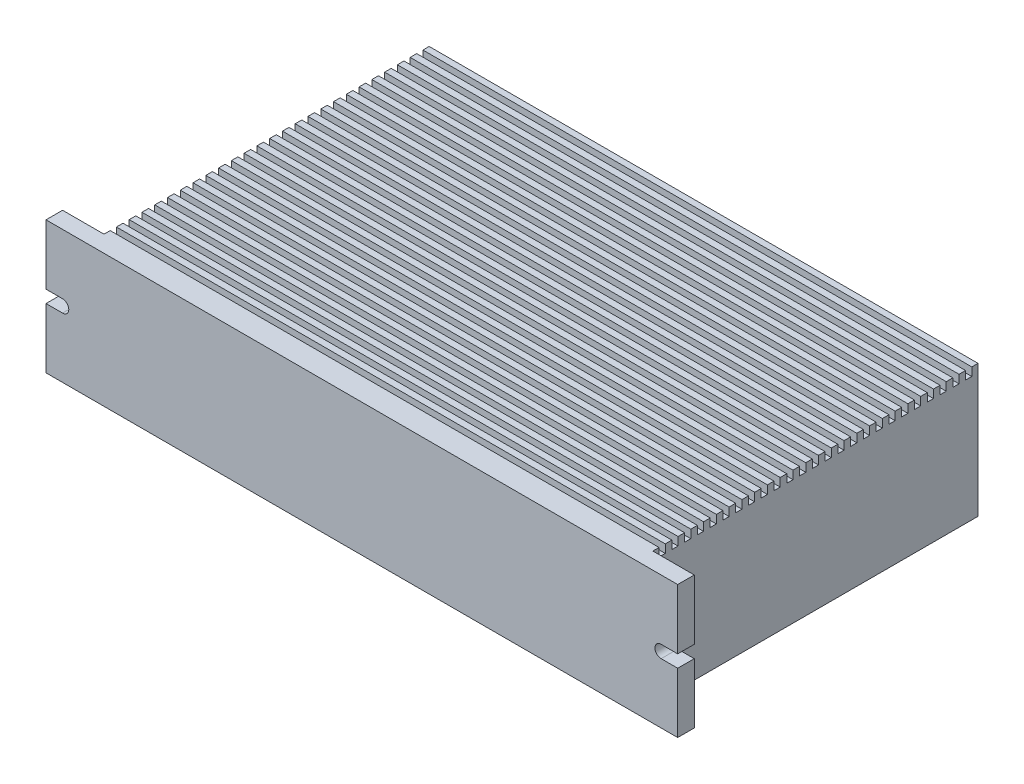
SolidWorks part; units mm, degrees
material "1060 合金"
ref_plane "前视基准面" through (0, 0, 0) normal (0, 0, 1) x (1, 0, 0)
ref_plane "上视基准面" through (0, 0, 0) normal (0, 1, 0) x (1, 0, 0)
ref_plane "右视基准面" through (0, 0, 0) normal (1, 0, 0) x (0, 0, -1)
sketch "草图1" plane through (0, 0, 0) normal (0, 1, 0) x (1, 0, 0)
  line L1 (-132.5, 82.5) -> (132.5, 82.5)
  line L2 (-132.5, 82.5) -> (-132.5, -82.5)
  line L3 (-132.5, -82.5) -> (132.5, -82.5)
  line L4 (132.5, 82.5) -> (132.5, -82.5)
  point P4 (-132.5, 0)
  point P6 (0, 82.5)
  dimension "D1" = 165
  dimension "D2" = 265
extrude "凸台-拉伸1" add sketch "草图1" along normal blind 64
sketch "草图2" plane through (0, 0, 82.5) normal (0, 0, 1) x (1, 0, 0)
  line L1 (-152.5, 64) -> (152.5, 64)
  line L2 (-152.5, 64) -> (-152.5, 35)
  line L3 (-152.5, 0) -> (152.5, 0)
  line L4 (152.5, 64) -> (152.5, 35)
  line L5 (-132.5, 64) -> (-132.5, 0) construction
  line L6 (-132.5, 0) -> (132.5, 0) construction
  line L7 (-132.5, 64) -> (132.5, 64) construction
  line L8 (152.5, 29) -> (152.5, 0)
  line L9 (-152.5, 35) -> (-144.5, 35)
  line L10 (-152.5, 29) -> (-144.5, 29)
  line L11 (0, 0) -> (0, 64) construction
  line L14 (-152.5, 35) -> (-144.5, 35)
  line L15 (-152.5, 29) -> (-144.5, 29)
  line L17 (152.5, 29) -> (144.5, 29)
  line L18 (152.5, 35) -> (144.5, 35)
  line L19 (152.5, 29) -> (144.5, 29)
  line L20 (152.5, 35) -> (144.5, 35)
  line L21 (-152.5, 29) -> (-152.5, 0)
  arc A1 (-144.5, 29) -> (-144.5, 35) centre (-144.5, 32) ccw
  arc A4 (144.5, 29) -> (144.5, 35) centre (144.5, 32) cw
  line M6 (132.5, 0) -> (132.5, 64)
  line M8 (-132.5, 64) -> (-132.5, 0)
  dimension "D3" = 3
  dimension "D1" = 29
  dimension "D2" = 20
  dimension "D4" = 8
extrude "凸台-拉伸2" add sketch "草图2" against normal blind 8 contours A1 L10 L21 L3 L1 L2 L9 M8 | L17 A4 L18 L4 L1 L3 L8 M6
sketch "草图3" plane through (0, 0, 0) normal (1, 0, 0) x (0, 0, -1)
  line L0 (-74.5, 64) -> (82.5, 64) construction
  line L1 (-71.5, 64) -> (-68.5, 64)
  line L2 (-71.5, 64) -> (-71.5, 60)
  line L3 (-71.5, 60) -> (-68.5, 60)
  line L4 (-68.5, 64) -> (-68.5, 60)
  line L5 (-74.5, 64) -> (-74.5, 35) construction
  line L6 (-65.3333, 60) -> (-62.3333, 60)
  line L7 (-62.3333, 64) -> (-62.3333, 60)
  line L8 (-65.3333, 64) -> (-62.3333, 64)
  line L9 (-65.3333, 64) -> (-65.3333, 60)
  line L10 (-59.1667, 60) -> (-56.1667, 60)
  line L11 (-56.1667, 64) -> (-56.1667, 60)
  line L12 (-59.1667, 64) -> (-56.1667, 64)
  line L13 (-59.1667, 64) -> (-59.1667, 60)
  line L14 (-53, 60) -> (-50, 60)
  line L15 (-50, 64) -> (-50, 60)
  line L16 (-53, 64) -> (-50, 64)
  line L17 (-53, 64) -> (-53, 60)
  line L18 (-46.8333, 60) -> (-43.8333, 60)
  line L19 (-43.8333, 64) -> (-43.8333, 60)
  line L20 (-46.8333, 64) -> (-43.8333, 64)
  line L21 (-46.8333, 64) -> (-46.8333, 60)
  line L22 (-40.6667, 60) -> (-37.6667, 60)
  line L23 (-37.6667, 64) -> (-37.6667, 60)
  line L24 (-40.6667, 64) -> (-37.6667, 64)
  line L25 (-40.6667, 64) -> (-40.6667, 60)
  line L26 (-34.5, 60) -> (-31.5, 60)
  line L27 (-31.5, 64) -> (-31.5, 60)
  line L28 (-34.5, 64) -> (-31.5, 64)
  line L29 (-34.5, 64) -> (-34.5, 60)
  line L30 (-28.3333, 60) -> (-25.3333, 60)
  line L31 (-25.3333, 64) -> (-25.3333, 60)
  line L32 (-28.3333, 64) -> (-25.3333, 64)
  line L33 (-28.3333, 64) -> (-28.3333, 60)
  line L34 (-22.1667, 60) -> (-19.1667, 60)
  line L35 (-19.1667, 64) -> (-19.1667, 60)
  line L36 (-22.1667, 64) -> (-19.1667, 64)
  line L37 (-22.1667, 64) -> (-22.1667, 60)
  line L38 (-16, 60) -> (-13, 60)
  line L39 (-13, 64) -> (-13, 60)
  line L40 (-16, 64) -> (-13, 64)
  line L41 (-16, 64) -> (-16, 60)
  line L42 (-9.8333, 60) -> (-6.8333, 60)
  line L43 (-6.8333, 64) -> (-6.8333, 60)
  line L44 (-9.8333, 64) -> (-6.8333, 64)
  line L45 (-9.8333, 64) -> (-9.8333, 60)
  line L46 (-3.6667, 60) -> (-0.6667, 60)
  line L47 (-0.6667, 64) -> (-0.6667, 60)
  line L48 (-3.6667, 64) -> (-0.6667, 64)
  line L49 (-3.6667, 64) -> (-3.6667, 60)
  line L50 (2.5, 60) -> (5.5, 60)
  line L51 (5.5, 64) -> (5.5, 60)
  line L52 (2.5, 64) -> (5.5, 64)
  line L53 (2.5, 64) -> (2.5, 60)
  line L54 (8.6667, 60) -> (11.6667, 60)
  line L55 (11.6667, 64) -> (11.6667, 60)
  line L56 (8.6667, 64) -> (11.6667, 64)
  line L57 (8.6667, 64) -> (8.6667, 60)
  line L58 (14.8333, 60) -> (17.8333, 60)
  line L59 (17.8333, 64) -> (17.8333, 60)
  line L60 (14.8333, 64) -> (17.8333, 64)
  line L61 (14.8333, 64) -> (14.8333, 60)
  line L62 (21, 60) -> (24, 60)
  line L63 (24, 64) -> (24, 60)
  line L64 (21, 64) -> (24, 64)
  line L65 (21, 64) -> (21, 60)
  line L66 (27.1667, 60) -> (30.1667, 60)
  line L67 (30.1667, 64) -> (30.1667, 60)
  line L68 (27.1667, 64) -> (30.1667, 64)
  line L69 (27.1667, 64) -> (27.1667, 60)
  line L70 (33.3333, 60) -> (36.3333, 60)
  line L71 (36.3333, 64) -> (36.3333, 60)
  line L72 (33.3333, 64) -> (36.3333, 64)
  line L73 (33.3333, 64) -> (33.3333, 60)
  line L74 (39.5, 60) -> (42.5, 60)
  line L75 (42.5, 64) -> (42.5, 60)
  line L76 (39.5, 64) -> (42.5, 64)
  line L77 (39.5, 64) -> (39.5, 60)
  line L78 (45.6667, 60) -> (48.6667, 60)
  line L79 (48.6667, 64) -> (48.6667, 60)
  line L80 (45.6667, 64) -> (48.6667, 64)
  line L81 (45.6667, 64) -> (45.6667, 60)
  line L82 (51.8333, 60) -> (54.8333, 60)
  line L83 (54.8333, 64) -> (54.8333, 60)
  line L84 (51.8333, 64) -> (54.8333, 64)
  line L85 (51.8333, 64) -> (51.8333, 60)
  line L86 (58, 60) -> (61, 60)
  line L87 (61, 64) -> (61, 60)
  line L88 (58, 64) -> (61, 64)
  line L89 (58, 64) -> (58, 60)
  line L90 (64.1667, 60) -> (67.1667, 60)
  line L91 (67.1667, 64) -> (67.1667, 60)
  line L92 (64.1667, 64) -> (67.1667, 64)
  line L93 (64.1667, 64) -> (64.1667, 60)
  line L94 (70.3333, 60) -> (73.3333, 60)
  line L95 (73.3333, 64) -> (73.3333, 60)
  line L96 (70.3333, 64) -> (73.3333, 64)
  line L97 (70.3333, 64) -> (70.3333, 60)
  line L98 (76.5, 60) -> (79.5, 60)
  line L99 (79.5, 64) -> (79.5, 60)
  line L100 (76.5, 64) -> (79.5, 64)
  line L101 (76.5, 64) -> (76.5, 60)
  line L102 (82.5, 64) -> (82.5, 0) construction
  dimension "D1" = 3
  dimension "D2" = 3
  dimension "D3" = 4
  dimension "D5" = 3
  dimension "D4" = 25
extrude "切除-拉伸1" cut sketch "草图3" against normal through all both and the other way through all
sketch "草图4" plane through (0, 0, 0) normal (1, 0, 0) x (0, 0, -1)
  line L0 (82.5, 64) -> (82.5, 0) construction
  line L1 (-66.5, 52) -> (74.5, 52)
  line L2 (-66.5, 52) -> (-66.5, 8)
  line L3 (-66.5, 8) -> (74.5, 8)
  line L4 (74.5, 52) -> (74.5, 8)
  line L5 (-74.5, 0) -> (-74.5, 64) construction
  line L6 (-74.5, 0) -> (82.5, 0) construction
  line L7 (-50, 60) -> (-53, 60) construction
  point P12 (-51.5, 60)
  dimension "D1" = 8
  dimension "D2" = 8
  dimension "D3" = 8
  dimension "D4" = 8
extrude "切除-拉伸2" cut sketch "草图4" against normal mid plane 240
